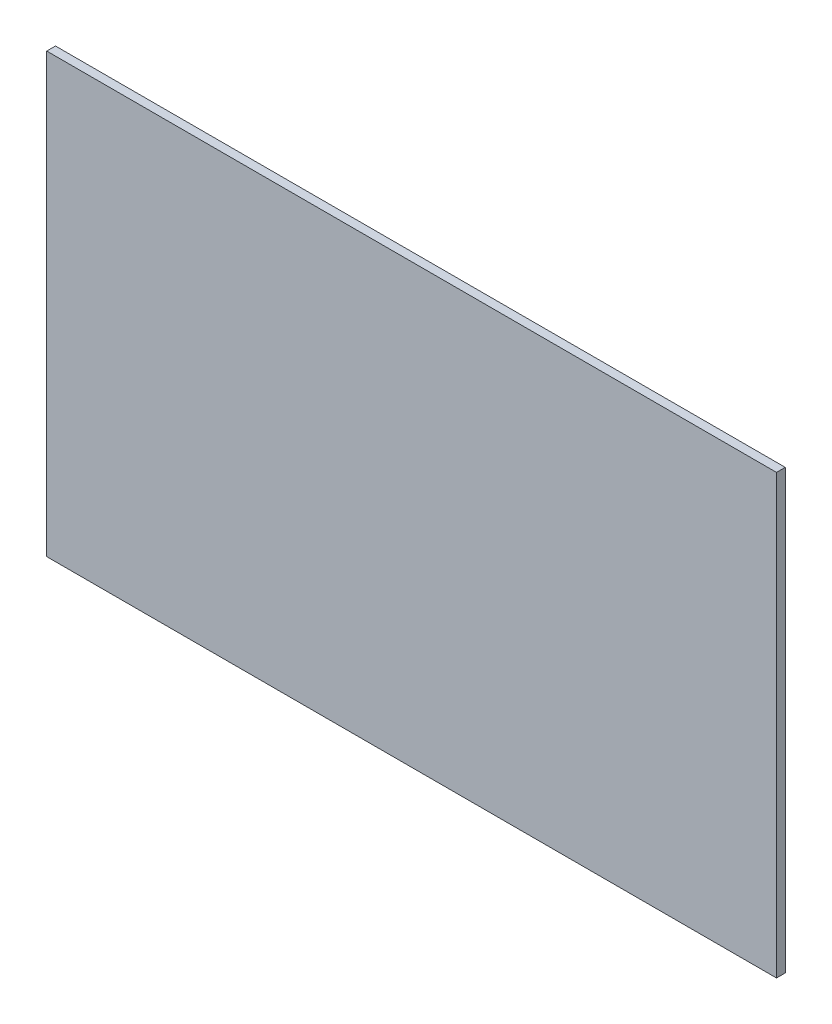
SolidWorks part; units mm, degrees
ref_plane "Front Plane" through (0, 0, 0) normal (0, 0, 1) x (1, 0, 0)
ref_plane "Top Plane" through (0, 0, 0) normal (0, 1, 0) x (1, 0, 0)
ref_plane "Right Plane" through (0, 0, 0) normal (1, 0, 0) x (0, 0, -1)
sketch "Sketch1" plane through (0, 0, 0) normal (0, 0, 1) x (1, 0, 0)
  line L1 (-125, 77.0631) -> (125, 77.0631)
  line L2 (-125, 77.0631) -> (-125, -72.9369)
  line L3 (-125, -72.9369) -> (125, -72.9369)
  line L4 (125, 77.0631) -> (125, -72.9369)
  dimension "D1" = 250
  dimension "D2" = 150
extrude "Boss-Extrude1" add sketch "Sketch1" along normal blind 3
